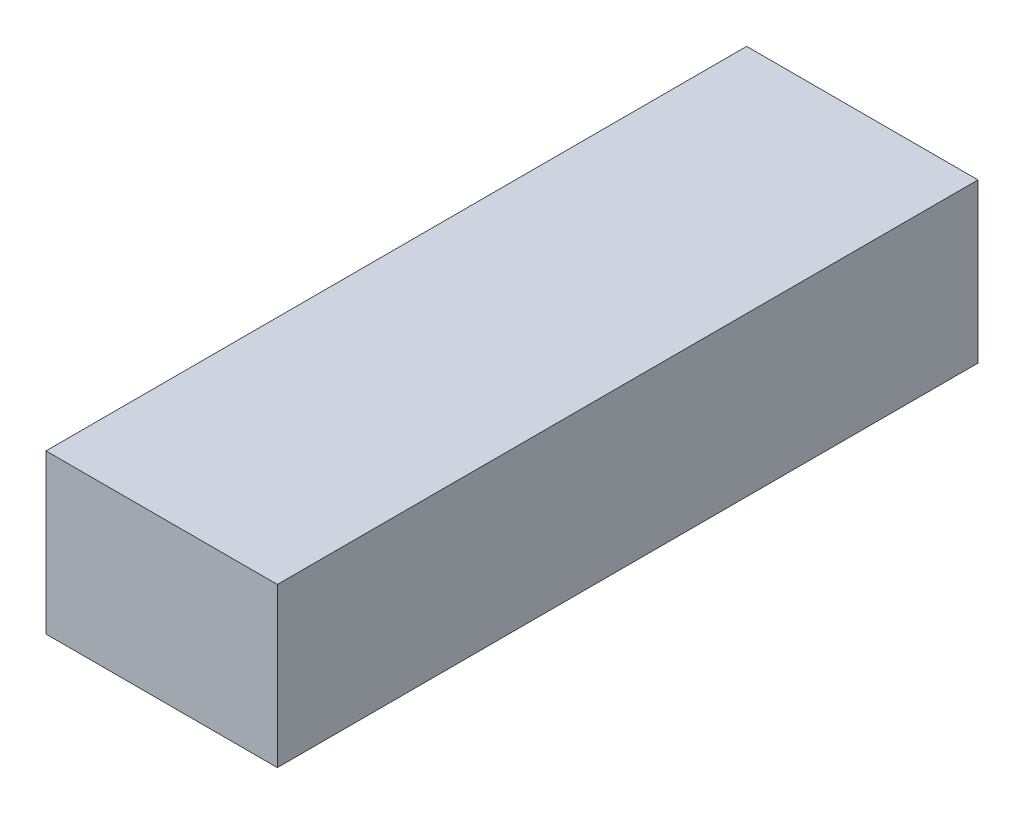
SolidWorks part; units mm, degrees
ref_plane "Front Plane" through (0, 0, 0) normal (0, 0, 1) x (1, 0, 0)
ref_plane "Top Plane" through (0, 0, 0) normal (0, 1, 0) x (1, 0, 0)
ref_plane "Right Plane" through (0, 0, 0) normal (1, 0, 0) x (0, 0, -1)
sketch "Sketch1" plane through (0, 0, 0) normal (0, 0, 1) x (1, 0, 0)
  line L1 (-17.5, -12) -> (17.5, -12)
  line L2 (-17.5, -12) -> (-17.5, 12)
  line L3 (-17.5, 12) -> (17.5, 12)
  line L4 (17.5, -12) -> (17.5, 12)
  line L5 (-17.5, -12) -> (17.5, 12) construction
  line L6 (-17.5, 12) -> (17.5, -12) construction
  point P0 (0, 0)
  dimension "D1" = 35
  dimension "D2" = 24
extrude "Boss-Extrude1" add sketch "Sketch1" along normal blind 106
